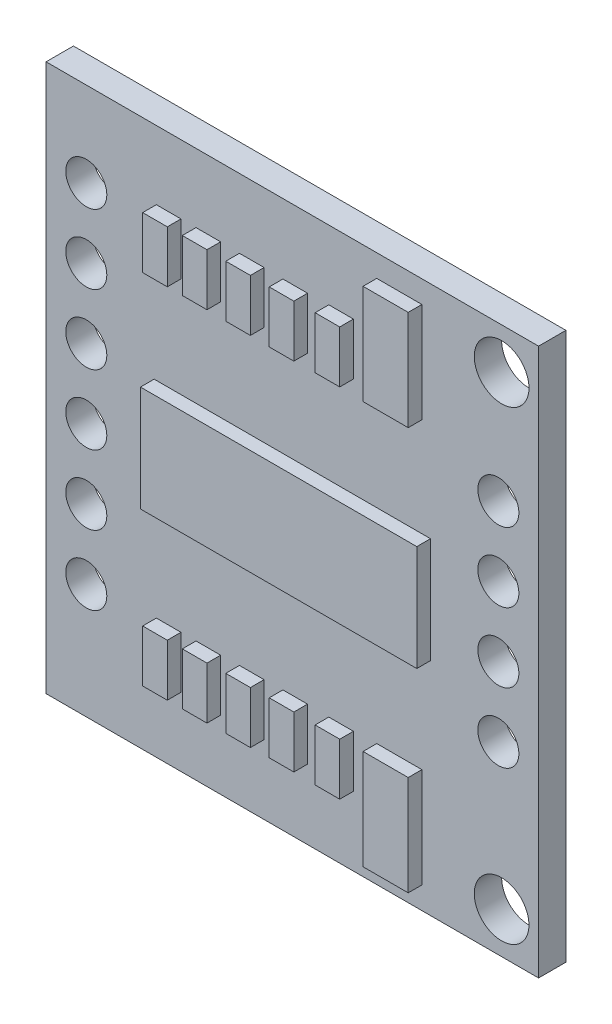
SolidWorks part; units mm, degrees
ref_plane "Front Plane" through (0, 0, 0) normal (0, 0, 1) x (1, 0, 0)
ref_plane "Top Plane" through (0, 0, 0) normal (0, 1, 0) x (1, 0, 0)
ref_plane "Right Plane" through (0, 0, 0) normal (1, 0, 0) x (0, 0, -1)
sketch "Sketch1" plane through (0, 0, 0) normal (0, 0, 1) x (1, 0, 0)
  line L0 (-19.3754, 0) -> (17.882, 0) construction
  line L1 (-9, -10) -> (9, -10)
  line L2 (-9, -10) -> (-9, 10)
  line L3 (-9, 10) -> (9, 10)
  line L4 (9, -10) -> (9, 10)
  line L5 (-9, -10) -> (9, 10) construction
  line L6 (-9, 10) -> (9, -10) construction
  circle A0 centre (7.65, 8.5) radius 1
  circle A1 centre (7.65, -8.5) radius 1
  point P0 (0, 0)
  dimension "D3" = 2
  dimension "D1" = 18
  dimension "D2" = 20
  dimension "D4" = 1.5
  dimension "D5" = 1.35
extrude "Boss-Extrude1" add sketch "Sketch1" along normal blind 1
sketch "Sketch2" plane through (0, 0, 1) normal (0, 0, 1) x (1, 0, 0)
  line L0 (9, 10) -> (-9, 10) construction
  line L1 (-9, 10) -> (-9, -10) construction
  line L2 (0, -9.7175) -> (0, 9.6093) construction
  circle A0 centre (-7.53, 6.9) radius 0.75
  circle A1 centre (-7.53, 4.36) radius 0.75
  circle A2 centre (-7.53, 1.82) radius 0.75
  circle A3 centre (-7.53, -0.72) radius 0.75
  circle A4 centre (-7.53, -3.26) radius 0.75
  circle A5 centre (-7.53, -5.8) radius 0.75
  circle A6 centre (7.53, -3.26) radius 0.75
  circle A7 centre (7.53, -0.72) radius 0.75
  circle A8 centre (7.53, 1.82) radius 0.75
  circle A9 centre (7.53, 4.36) radius 0.75
  dimension "D1" = 1.5
  dimension "D2" = 1.5
  dimension "D3" = 1.5
  dimension "D4" = 1.5
  dimension "D5" = 1.5
  dimension "D6" = 1.5
  dimension "D7" = 2.54
  dimension "D8" = 2.54
  dimension "D9" = 2.54
  dimension "D10" = 2.54
  dimension "D11" = 2.54
  dimension "D12" = 3.1
  dimension "D13" = 1.47
  dimension "D14" = 1.47
  dimension "D15" = 1.47
  dimension "D16" = 1.47
  dimension "D17" = 1.47
  dimension "D18" = 1.47
extrude "Cut-Extrude1" cut sketch "Sketch2" against normal blind 1
sketch "Sketch3" plane through (0, 0, 1) normal (0, 0, 1) x (1, 0, 0)
  line L5 (5.05, -1.93) -> (-5.05, -1.93)
  line L6 (5.05, -1.93) -> (5.05, 1.93)
  line L7 (5.05, 1.93) -> (-5.05, 1.93)
  line L8 (-5.05, -1.93) -> (-5.05, 1.93)
  line L9 (5.05, -1.93) -> (-5.05, 1.93) construction
  line L10 (5.05, 1.93) -> (-5.05, -1.93) construction
  point P0 (0, 0)
  dimension "D1" = 10.1
  dimension "D2" = 3.86
extrude "Boss-Extrude3" add sketch "Sketch3" along normal blind 0.5 contours L6 L5 L8 L7
sketch "Sketch4" plane through (0, 0, 1) normal (0, 0, 1) x (1, 0, 0)
  line L0 (-5.05, 1.93) -> (-5.05, 8.2392) construction
  line L1 (3.0853, 9.1869) -> (4.7353, 9.1869)
  line L2 (3.0853, 9.1869) -> (3.0853, 5.5369)
  line L3 (3.0853, 5.5369) -> (4.7353, 5.5369)
  line L4 (4.7353, 9.1869) -> (4.7353, 5.5369)
  line L5 (3.0853, 9.1869) -> (4.7353, 5.5369) construction
  line L6 (3.0853, 5.5369) -> (4.7353, 9.1869) construction
  line L11 (0.5556, 7.4529) -> (-0.3444, 7.4529)
  line L12 (0.5556, 7.4529) -> (0.5556, 5.5529)
  line L13 (2.2326, 7.4743) -> (1.3326, 7.4743)
  line L14 (2.2326, 7.4743) -> (2.2326, 5.5743)
  line L15 (2.2326, 5.5743) -> (1.3326, 5.5743)
  line L16 (1.3326, 7.4743) -> (1.3326, 5.5743)
  line L17 (2.2326, 7.4743) -> (1.3326, 5.5743) construction
  line L18 (2.2326, 5.5743) -> (1.3326, 7.4743) construction
  line L23 (0.5556, 5.5529) -> (-0.3444, 5.5529)
  line L24 (-0.3444, 7.4529) -> (-0.3444, 5.5529)
  line L29 (-1.0322, 7.4725) -> (-1.9322, 7.4725)
  line L30 (-1.0322, 7.4725) -> (-1.0322, 5.5725)
  line L35 (-1.0322, 5.5725) -> (-1.9322, 5.5725)
  line L36 (-1.9322, 7.4725) -> (-1.9322, 5.5725)
  line L37 (-2.6201, 7.4921) -> (-3.5201, 7.4921)
  line L38 (-2.6201, 7.4921) -> (-2.6201, 5.5921)
  line L39 (-2.6201, 5.5921) -> (-3.5201, 5.5921)
  line L40 (-3.5201, 7.4921) -> (-3.5201, 5.5921)
  line L41 (-4.0698, 7.4921) -> (-4.9698, 7.4921)
  line L42 (-4.0698, 7.4921) -> (-4.0698, 5.5921)
  line L43 (-4.0698, 5.5921) -> (-4.9698, 5.5921)
  line L44 (-4.9698, 7.4921) -> (-4.9698, 5.5921)
  line L45 (0, 0) -> (-12.9978, 0) construction
  line L46 (0, 0) -> (11.7026, 0) construction
  line L47 (3.0853, -5.5369) -> (4.7353, -5.5369)
  line L48 (4.7353, -9.1869) -> (4.7353, -5.5369)
  line L49 (3.0853, -9.1869) -> (4.7353, -9.1869)
  line L50 (3.0853, -9.1869) -> (3.0853, -5.5369)
  line L51 (2.2326, -5.5743) -> (1.3326, -5.5743)
  line L52 (1.3326, -7.4743) -> (1.3326, -5.5743)
  line L53 (2.2326, -7.4743) -> (1.3326, -7.4743)
  line L54 (2.2326, -7.4743) -> (2.2326, -5.5743)
  line L55 (0.5556, -7.4529) -> (0.5556, -5.5529)
  line L56 (0.5556, -5.5529) -> (-0.3444, -5.5529)
  line L57 (-0.3444, -7.4529) -> (-0.3444, -5.5529)
  line L58 (0.5556, -7.4529) -> (-0.3444, -7.4529)
  line L59 (-1.0322, -7.4725) -> (-1.0322, -5.5725)
  line L60 (-1.0322, -5.5725) -> (-1.9322, -5.5725)
  line L61 (-1.9322, -7.4725) -> (-1.9322, -5.5725)
  line L62 (-1.0322, -7.4725) -> (-1.9322, -7.4725)
  line L63 (-2.6201, -7.4921) -> (-2.6201, -5.5921)
  line L64 (-2.6201, -5.5921) -> (-3.5201, -5.5921)
  line L65 (-3.5201, -7.4921) -> (-3.5201, -5.5921)
  line L66 (-2.6201, -7.4921) -> (-3.5201, -7.4921)
  line L67 (-4.0698, -7.4921) -> (-4.0698, -5.5921)
  line L68 (-4.0698, -5.5921) -> (-4.9698, -5.5921)
  line L69 (-4.9698, -7.4921) -> (-4.9698, -5.5921)
  line L70 (-4.0698, -7.4921) -> (-4.9698, -7.4921)
  point P0 (3.9103, 7.3619)
  point P10 (1.7826, 6.5243)
  dimension "D1" = 3.65
  dimension "D3" = 1.65
  dimension "D6" = 1.9
  dimension "D7" = 0.9
extrude "Boss-Extrude4" add sketch "Sketch4" along normal blind 0.5 contours L41 L44 L43 L42 | L37 L40 L39 L38 | L29 L36 L35 L30 | L11 L24 L23 L12 | L13 L16 L15 L14 | L2 L1 L4 L3 | L47 L48 L49 L50 | L51 L52 L53 L54 | L55 L56 L57 L58 | L59 L60 L61 L62 | L63 L64 L65 L66 | L67 L68 L69 L70
